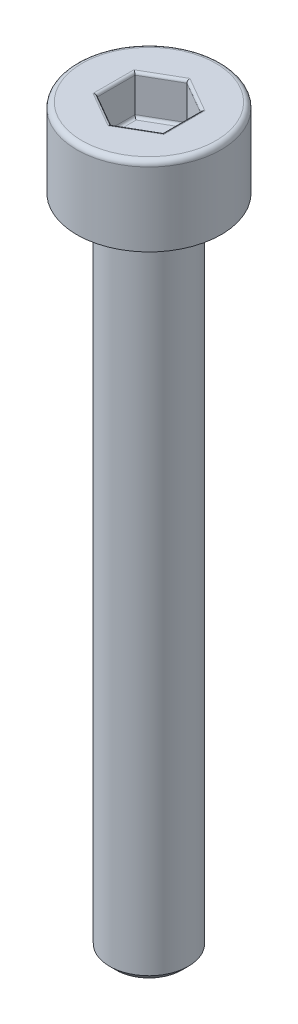
SolidWorks part; units mm, degrees
ref_plane "Front Plane" through (0, 0, 0) normal (0, 0, 1) x (1, 0, 0)
ref_plane "Top Plane" through (0, 0, 0) normal (0, 1, 0) x (1, 0, 0)
ref_plane "Right Plane" through (0, 0, 0) normal (1, 0, 0) x (0, 0, -1)
sketch "Sketch1" plane through (0, 0, 0) normal (0, 0, 1) x (1, 0, 0)
  line L0 (0, 0) -> (0, -47.0967) construction
  line L1 (0, -28) -> (-1.5, -28)
  line L2 (-1.5, -28) -> (-1.5, -3)
  line L3 (-1.5, -3) -> (-2.75, -3)
  line L4 (-2.75, -3) -> (-2.75, 0)
  line L5 (-2.75, 0) -> (0, 0)
  line L6 (0, 0) -> (0, -28)
  dimension "d" = 3
  dimension "l" = 28
  dimension "k" = 3
  dimension "dk" = 5.5
revolve "Revolve1" add sketch "Sketch1" angle 360 about L0
chamfer "Chamfer1" distance 0.25 angle 45 2 edges at (0, -3, 1.5) (0, -28, 1.5)
fillet "Fillet1" radius 0.2 1 edges at (0, 0, 2.75)
sketch "Sketch2" plane through (0, 0, 0) normal (0, 1, 0) x (1, 0, 0)
  line L1 (0, 1.4434) -> (-1.25, 0.7217)
  line L2 (-1.25, 0.7217) -> (-1.25, -0.7217)
  line L3 (-1.25, -0.7217) -> (0, -1.4434)
  line L4 (0, -1.4434) -> (1.25, -0.7217)
  line L5 (1.25, -0.7217) -> (1.25, 0.7217)
  line L6 (1.25, 0.7217) -> (0, 1.4434)
  circle A0 centre (0, 0) radius 1.25 construction
  dimension "s" = 2.5
extrude "Cut-Extrude1" cut sketch "Sketch2" against normal blind 1.5
fillet "Fillet2" radius 0.1 12 edges at (-0.625, 0, -1.0825) (-1.25, 0, 0) (-0.625, 0, 1.0825) (0.625, 0, 1.0825) (1.25, 0, 0) (0.625, 0, -1.0825) (1.25, -1.5, 0) (0.625, -1.5, 1.0825) (-0.625, -1.5, 1.0825) (-1.25, -1.5, 0) (-0.625, -1.5, -1.0825) (0.625, -1.5, -1.0825)
